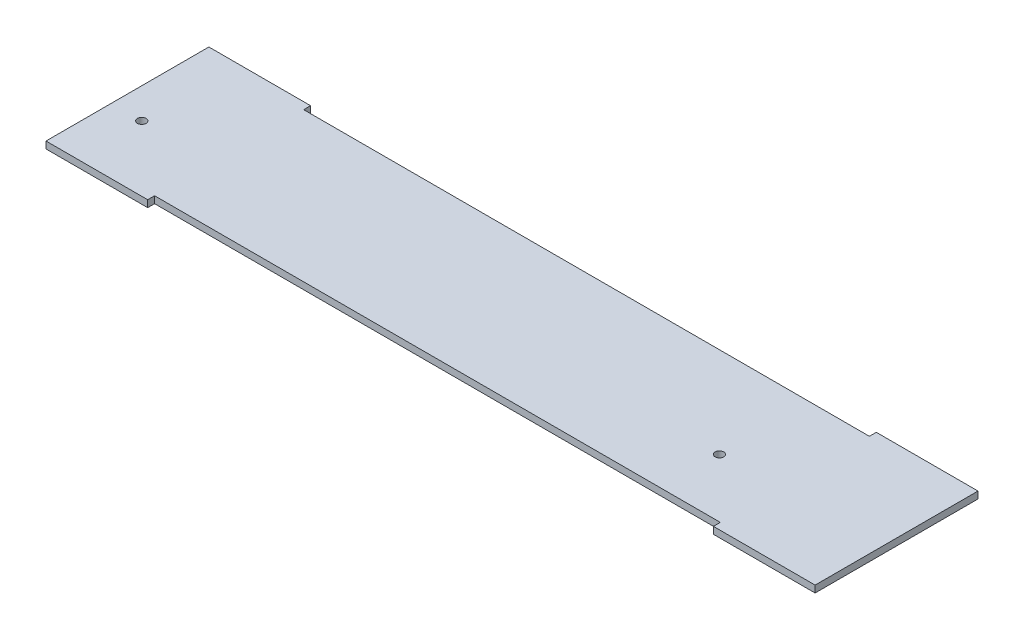
SolidWorks part; units mm, degrees
ref_plane "Front Plane" through (0, 0, 0) normal (0, 0, 1) x (1, 0, 0)
ref_plane "Top Plane" through (0, 0, 0) normal (0, 1, 0) x (1, 0, 0)
ref_plane "Right Plane" through (0, 0, 0) normal (1, 0, 0) x (0, 0, -1)
other "Default"
sketch "Sketch1" plane through (0, 0, 0) normal (0, 1, 0) x (1, 0, 0)
  line L0 (-354.15, 75) -> (-354.15, -75)
  line L1 (-354.15, -75) -> (-260.5, -75)
  line L2 (-260.5, -75) -> (-260.5, -68.65)
  line L3 (-260.5, -68.65) -> (260.5, -68.65)
  line L4 (260.5, -68.65) -> (260.5, -75)
  line L5 (260.5, -75) -> (354.15, -75)
  line L6 (354.15, -75) -> (354.15, 75)
  line L7 (354.15, 75) -> (260.5, 75)
  line L8 (260.5, 75) -> (260.5, 68.65)
  line L9 (260.5, 68.65) -> (-260.5, 68.65)
  line L10 (-260.5, 68.65) -> (-260.5, 75)
  line L11 (-260.5, 75) -> (-354.15, 75)
  point P11 (0, -68.65)
  point P13 (354.15, 0)
  dimension "D1" = 150
  dimension "D2" = 6.35
  dimension "TabWidth" = 93.65
  dimension "Width" = 708.3
extrude "Boss-Extrude1" add sketch "Sketch1" along normal mid plane 6.35
sketch "Sketch2" [suppressed] plane through (0, 3.175, 0) normal (0, 1, 0) x (1, 0, 0)
  line L0 (233.15, -86.7757) -> (233.15, 92.4765) construction
  line L1 (95.15, -19.35) -> (178.15, -19.35) construction
  line L2 (95.15, -19.35) -> (95.15, 58.65) construction
  line L3 (95.15, 58.65) -> (178.15, 58.65) construction
  line L4 (178.15, -19.35) -> (178.15, 58.65) construction
  line L5 (95.15, -19.35) -> (178.15, 58.65) construction
  line L6 (95.15, 58.65) -> (178.15, -19.35) construction
  line L7 (188.15, 88.359) -> (188.15, -110.3451) construction
  line L8 (-49.46, 51.57) -> (-49.46, 61.57) construction
  line L9 (90.15, -24.35) -> (90.15, 63.65)
  line L10 (90.15, 63.65) -> (183.15, 63.65)
  line L11 (183.15, -24.35) -> (183.15, 63.65)
  line L12 (90.15, -24.35) -> (183.15, -24.35)
  line L13 (239.5, -75) -> (239.5, 75) construction
  line L14 (38.15, -90.5492) -> (38.15, 114.8099) construction
  line L15 (47.45, 44.65) -> (69.75, 44.65) construction
  line L16 (47.45, 44.65) -> (47.45, -5.35) construction
  line L17 (47.45, -5.35) -> (69.75, -5.35) construction
  line L18 (69.75, 44.65) -> (69.75, -5.35) construction
  line L19 (44.45, 47.65) -> (44.45, -8.35)
  line L20 (44.45, -8.35) -> (72.75, -8.35)
  line L21 (72.75, 47.65) -> (72.75, -8.35)
  line L22 (44.45, 47.65) -> (72.75, 47.65)
  line L23 (139.5, 68.65) -> (-139.5, 68.65) construction
  line L24 (-80.91, -8.28) -> (18.15, -8.28) construction
  line L25 (-80.91, -8.28) -> (-80.91, 66.65) construction
  line L26 (-80.91, 66.65) -> (18.15, 66.65) construction
  line L27 (18.15, -8.28) -> (18.15, 66.65) construction
  line L28 (-80.91, -8.28) -> (18.15, 66.65) construction
  line L29 (-80.91, 66.65) -> (18.15, -8.28) construction
  line L30 (-75.83, -3.2) -> (13.07, -3.2) construction
  line L31 (-75.83, -3.2) -> (-75.83, 61.57) construction
  line L32 (-75.83, 61.57) -> (13.07, 61.57) construction
  line L33 (13.07, -3.2) -> (13.07, 61.57) construction
  line L34 (-75.83, -3.2) -> (13.07, 61.57) construction
  line L35 (-75.83, 61.57) -> (13.07, -3.2) construction
  line L36 (-155.36, 15.85) -> (-110.91, 15.85) construction
  line L37 (-155.36, 15.85) -> (-155.36, 66.65) construction
  line L38 (-155.36, 66.65) -> (-110.91, 66.65) construction
  line L39 (-110.91, 15.85) -> (-110.91, 66.65) construction
  line L40 (-155.36, 15.85) -> (-110.91, 66.65) construction
  line L41 (-155.36, 66.65) -> (-110.91, 15.85) construction
  line L42 (-151.55, 19.66) -> (-114.72, 19.66) construction
  line L43 (-151.55, 19.66) -> (-151.55, 62.84) construction
  line L44 (-151.55, 62.84) -> (-114.72, 62.84) construction
  line L45 (-114.72, 19.66) -> (-114.72, 62.84) construction
  line L46 (-151.55, 19.66) -> (-114.72, 62.84) construction
  line L47 (-151.55, 62.84) -> (-114.72, 19.66) construction
  line L48 (-51.46, 51.57) -> (-51.46, 61.57)
  line L49 (-47.46, 51.57) -> (-47.46, 61.57)
  line L50 (-9.46, 51.57) -> (-9.46, 61.57) construction
  line L51 (-11.46, 51.57) -> (-11.46, 61.57)
  line L52 (-7.46, 51.57) -> (-7.46, 61.57)
  circle A0 centre (-75.83, 61.57) radius 1.375
  circle A1 centre (13.07, 61.57) radius 1.375
  circle A2 centre (13.07, -3.2) radius 1.375
  circle A3 centre (-75.83, -3.2) radius 1.375
  circle A4 centre (-42.81, -3.2) radius 1.375
  circle A6 centre (-114.72, 19.66) radius 1.375
  circle A7 centre (-151.55, 19.66) radius 1.375
  circle A8 centre (-151.55, 62.84) radius 1.375
  circle A9 centre (-114.72, 63.48) radius 1.375
  arc A10 (-51.46, 51.57) -> (-47.46, 51.57) centre (-49.46, 51.57) ccw
  arc A11 (-47.46, 61.57) -> (-51.46, 61.57) centre (-49.46, 61.57) ccw
  arc A12 (-11.46, 51.57) -> (-7.46, 51.57) centre (-9.46, 51.57) ccw
  arc A13 (-7.46, 61.57) -> (-11.46, 61.57) centre (-9.46, 61.57) ccw
  point P0 (136.65, 19.65)
  point P19 (69.75, 19.65)
  point P28 (-31.38, 29.185)
  point P33 (-31.38, 29.185)
  point P44 (-133.135, 41.25)
  point P49 (-133.135, 41.25)
  point P60 (-49.46, 56.57)
  point P67 (-9.46, 56.57)
  dimension "D17" = 2.75
  dimension "D25" = 0.64
  dimension "D27" = 2
  dimension "D1" = 83
  dimension "D2" = 78
  dimension "D3" = 10
  dimension "D4" = 6.35
  dimension "D5" = 10
  dimension "D7" = 22.3
  dimension "D8" = 50
  dimension "D9" = 150
  dimension "D10" = 9.3
  dimension "D12" = 45
  dimension "D13" = 99.06
  dimension "D14" = 74.93
  dimension "D15" = 88.9
  dimension "D16" = 64.77
  dimension "D18" = 2
  dimension "D19" = 20
  dimension "D20" = 33.02
  dimension "D21" = 50.8
  dimension "D22" = 44.45
  dimension "D23" = 36.83
  dimension "D24" = 43.18
  dimension "D26" = 30
  dimension "D28" = 26.37
  dimension "D29" = 22.53
  dimension "D30" = 10
  dimension "D6" = 5
  dimension "D11" = 3
extrude "Back Only" [suppressed] cut sketch "Sketch2" against normal through all
sketch "Sketch3" [suppressed] plane through (0, 3.175, 0) normal (0, 1, 0) x (1, 0, 0)
  line L0 (-225.15, 9.65) -> (-200.15, 9.65) construction
  line L1 (-230.15, -0.35) -> (-195.15, -0.35) construction
  line L2 (-230.15, -0.35) -> (-230.15, 19.65) construction
  line L3 (-230.15, 19.65) -> (-195.15, 19.65) construction
  line L4 (-195.15, -0.35) -> (-195.15, 19.65) construction
  line L5 (-230.15, -0.35) -> (-195.15, 19.65) construction
  line L6 (-230.15, 19.65) -> (-195.15, -0.35) construction
  line L9 (-233.15, -93.1255) -> (-233.15, 99.5323) construction
  line L10 (-239.5, 75) -> (-239.5, -75) construction
  line L11 (139.5, 68.65) -> (-139.5, 68.65) construction
  line L12 (0, -88.5309) -> (0, 117.3513) construction
  circle A1 centre (-200.15, 9.65) radius 2.5
  circle A2 centre (-225.15, 9.65) radius 2.5
  circle A3 centre (200.15, 9.65) radius 2.5
  circle A5 centre (225.15, 9.65) radius 2.5
  point P0 (-212.65, 9.65)
  dimension "D4" = 5
  dimension "D1" = 35
  dimension "D2" = 20
  dimension "D5" = 25
  dimension "D6" = 59
  dimension "D7" = 6.35
  dimension "D8" = 3
extrude "Front and Back" [suppressed] cut sketch "Sketch3" against normal through all
sketch "Sketch4" plane through (0, -3.175, 0) normal (0, -1, 0) x (1, 0, 0)
  line L0 (-329.1, -3.15) -> (-323.1, -3.15) construction
  line L1 (202.9, -3.15) -> (208.9, -3.15) construction
  line L2 (-329.1, -3.15) -> (-323.1, -3.15) construction
  line L3 (202.9, -3.15) -> (208.9, -3.15) construction
  circle A0 centre (-326.1, 14.85) radius 4
  circle A1 centre (205.9, 14.85) radius 4
  point P8 (205.9, -3.15)
  point P10 (-326.1, -3.15)
  dimension "D1" = 8
  dimension "D2" = 18
extrude "Left and Right" cut sketch "Sketch4" against normal through all
sketch "Sketch5" [suppressed] plane through (0, 3.175, 0) normal (0, 1, 0) x (1, 0, 0)
  line L0 (260.5, 68.65) -> (-260.5, 68.65) construction
  line L1 (-155.15, -23.35) -> (-53.15, -23.35) construction
  line L2 (-155.15, -23.35) -> (-155.15, 58.65) construction
  line L3 (-155.15, 58.65) -> (-53.15, 58.65) construction
  line L4 (-53.15, -23.35) -> (-53.15, 58.65) construction
  line L5 (-155.15, -23.35) -> (-53.15, 58.65) construction
  line L6 (-155.15, 58.65) -> (-53.15, -23.35) construction
  line L7 (-354.15, 75) -> (-354.15, -75) construction
  line L9 (-150.65, -28.85) -> (-57.65, -28.85)
  line L10 (-150.65, -28.85) -> (-150.65, 64.15)
  line L11 (-150.65, 64.15) -> (-57.65, 64.15)
  line L12 (-57.65, -28.85) -> (-57.65, 64.15)
  line L13 (-150.65, -28.85) -> (-57.65, 64.15) construction
  line L14 (-150.65, 64.15) -> (-57.65, -28.85) construction
  circle A0 centre (-155.15, 58.65) radius 2.5
  circle A1 centre (-53.15, 58.65) radius 2.5
  circle A2 centre (-53.15, -23.35) radius 2.5
  circle A3 centre (-155.15, -23.35) radius 2.5
  point P0 (-104.15, 17.65)
  point P13 (-104.15, 17.65)
  dimension "D3" = 5
  dimension "D1" = 102
  dimension "D2" = 82
  dimension "D4" = 10
  dimension "D5" = 250
  dimension "D6" = 93
extrude "Right Only" [suppressed] cut sketch "Sketch5" against normal through all
fillet "Right Only 2" [suppressed] radius 5
